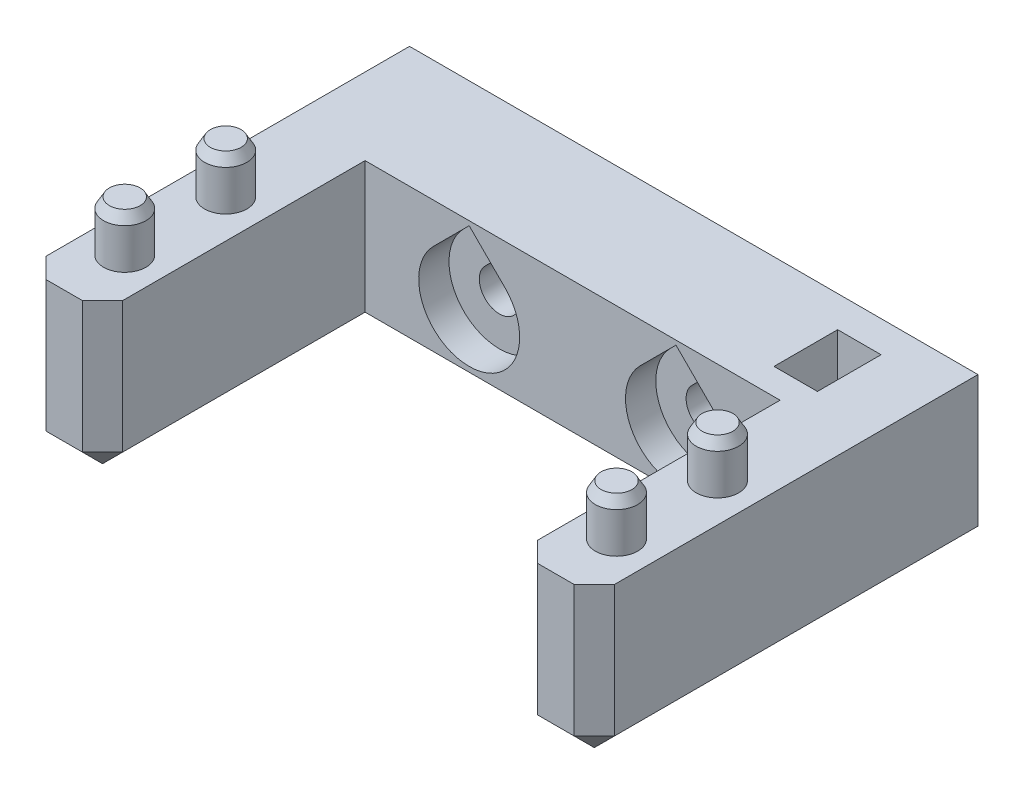
SolidWorks part; units mm, degrees
ref_plane "Front Plane" through (0, 0, 0) normal (0, 0, 1) x (1, 0, 0)
ref_plane "Top Plane" through (0, 0, 0) normal (0, 1, 0) x (1, 0, 0)
ref_plane "Right Plane" through (0, 0, 0) normal (1, 0, 0) x (0, 0, -1)
sketch "Sketch2" plane through (0, 0, 0) normal (0, 1, 0) x (1, 0, 0)
  line L0 (-22.25, 13.4082) -> (-22.25, -6080.7708) construction
  line L1 (-20.25, -10) -> (20.25, -10) construction
  line L2 (-20.25, -10) -> (-20.25, 10) construction
  line L3 (-20.25, 10) -> (20.25, 10) construction
  line L4 (20.25, -10) -> (20.25, 10) construction
  line L5 (-20.25, -10) -> (20.25, 10) construction
  line L6 (-20.25, 10) -> (20.25, -10) construction
  line L7 (0, 0) -> (-50000, 0) construction
  line L8 (-24.35, 2.9) -> (-24.35, -2.9) construction
  line L9 (0, 0) -> (0, 50000) construction
  circle A0 centre (-24.35, 5) radius 2.1
  circle A1 centre (-24.35, -5) radius 2.1
  circle A2 centre (24.35, -5) radius 2.1
  circle A3 centre (24.35, 5) radius 2.1
  point P0 (0, 0)
  point P12 (-24.35, 2.9)
  point P13 (-24.35, -2.9)
  point P18 (-24.35, 0)
  dimension "D2" = 4.2
  dimension "D1" = 2
  dimension "D3" = 40.5
  dimension "D4" = 20
  dimension "D5" = 5.8
extrude "Boss-Extrude1" add sketch "Sketch2" along normal blind 5
sketch "Sketch3" plane through (0, 0, 0) normal (0, 1, 0) x (1, 0, 0)
  line L0 (-20.25, -10) -> (-20.25, 10) construction
  line L1 (-28.15, -11) -> (-20.55, -11)
  line L2 (-28.15, -11) -> (-28.15, 15)
  line L3 (-28.15, 15) -> (-20.55, 15)
  line L4 (-20.55, -11) -> (-20.55, 15)
  line L5 (-28.15, -11) -> (-20.55, 15) construction
  line L6 (-28.15, 15) -> (-20.55, -11) construction
  line L7 (0, 0) -> (0, 50000) construction
  line L8 (28.15, -11) -> (28.15, 15)
  line L9 (28.15, -11) -> (20.55, -11)
  line L10 (20.55, -11) -> (20.55, 15)
  line L11 (28.15, 15) -> (20.55, 15)
  line L13 (200000, 0) -> (-250000, 0) construction
  point P0 (-24.35, 2)
  point P15 (0, 0)
  point P16 (-24.2905, 1.4461)
  point P17 (0, 0)
  point P18 (0, 0)
  point P22 (0, 0)
  dimension "D1" = 0.3
  dimension "D2" = 26
  dimension "D3" = 11
extrude "Boss-Extrude2" add sketch "Sketch3" against normal blind 15
chamfer "Chamfer1" distance 1 angle 30 2 edges at (-24.35, 5, -2.9) (-24.35, 5, 7.1)
chamfer "Chamfer2" distance 1 angle 30 2 edges at (24.35, 5, 2.9) (24.35, 5, -7.1)
sketch "Sketch4" plane through (0, 0, 0) normal (0, 1, 0) x (1, 0, 0)
  line L0 (-28.15, 15) -> (28.15, 15)
  line L1 (-28.15, 15) -> (-28.15, 27)
  line L2 (28.15, 15) -> (28.15, 27)
  line L3 (-28.15, 27) -> (28.15, 27)
  line L4 (28.15, 15) -> (20.55, 15) construction
  dimension "D1" = 12
extrude "Boss-Extrude3" add sketch "Sketch4" against normal up to surface (15 mm away) up to face at (-24.35, -15, -2)
sketch "Sketch5" plane through (0, 0, -15) normal (0, 0, 1) x (1, 0, 0)
  line L0 (0, 0) -> (0, -15) construction
  line L1 (-20.55, -15) -> (20.55, -15) construction
  line L2 (-10.2402, -7.5) -> (0, -7.5) construction
  line L3 (0, 0) -> (0, -50000) construction
  line L4 (-10.2402, -7.5) -> (-11.6544, -6.0858) construction
  line L5 (-10.2402, -7.5) -> (-8.8259, -6.0858) construction
  line L6 (-10.2402, -7.5) -> (-10.2402, 0) construction
  line L7 (-20.55, 0) -> (20.55, 0) construction
  line L8 (-11.6544, -6.0858) -> (-10.2402, -4.6716)
  line L9 (-10.2402, -4.6716) -> (-8.8259, -6.0858)
  line L10 (11.6544, -6.0858) -> (10.2402, -4.6716)
  line L11 (10.2402, -4.6716) -> (8.8259, -6.0858)
  line L12 (0, -7.5) -> (10.2402, -7.5) construction
  circle A0 centre (-10.2402, -7.5) radius 2 construction
  arc A1 (-11.6544, -6.0858) -> (-8.8259, -6.0858) centre (-10.2402, -7.5) ccw
  arc A2 (11.6544, -6.0858) -> (8.8259, -6.0858) centre (10.2402, -7.5) cw
  dimension "D1" = 4
extrude "Cut-Extrude1" cut sketch "Sketch5" against normal through all contours L8 A1 L9 | A2 L10 L11
sketch "Sketch6" plane through (0, 0, -15) normal (0, 0, 1) x (1, 0, 0)
  line L29 (-6.7046, -3.9645) -> (-10.2402, -0.4289)
  line L30 (-10.2402, -0.4289) -> (-13.7757, -3.9645)
  line L31 (-6.7046, -3.9645) -> (-10.2402, -0.4289)
  line L32 (-10.2402, -0.4289) -> (-13.7757, -3.9645)
  line L38 (13.7757, -3.9645) -> (10.2402, -0.4289)
  line L39 (10.2402, -0.4289) -> (6.7046, -3.9645)
  line L40 (13.7757, -3.9645) -> (10.2402, -0.4289)
  line L41 (10.2402, -0.4289) -> (6.7046, -3.9645)
  arc A13 (-13.7757, -3.9645) -> (-6.7046, -3.9645) centre (-10.2402, -7.5) ccw
  arc A14 (-13.7757, -3.9645) -> (-6.7046, -3.9645) centre (-10.2402, -7.5) ccw
  arc A16 (6.7046, -3.9645) -> (13.7757, -3.9645) centre (10.2402, -7.5) ccw
  arc A17 (6.7046, -3.9645) -> (13.7757, -3.9645) centre (10.2402, -7.5) ccw
  dimension "D1" = 3
  dimension "D2" = 3
extrude "Cut-Extrude2" cut sketch "Sketch6" against normal blind 3
chamfer "Chamfer7" distance 2 angle 45 12 edges at (0, -15, -15) (20.55, -15, -2) (20.55, -7.5, 11) (24.35, -15, 11) (28.15, -7.5, 11) (28.15, -15, -8) (0, -15, -27) (-28.15, -15, -8) (-28.15, -7.5, 11) (-24.35, -15, 11) (-20.55, -15, -2) (-20.55, -7.5, 11)
sketch "Sketch7" plane through (0, 0, 0) normal (0, 1, 0) x (1, 0, 0)
  line L0 (-20.55, 15) -> (20.55, 15) construction
  line L1 (21.65, 23.9) -> (17.35, 23.9)
  line L2 (21.65, 23.9) -> (21.65, 17.6)
  line L3 (21.65, 17.6) -> (17.35, 17.6)
  line L4 (17.35, 23.9) -> (17.35, 17.6)
  line L5 (21.65, 23.9) -> (17.35, 17.6) construction
  line L6 (21.65, 17.6) -> (17.35, 23.9) construction
  line L7 (28.15, -9) -> (28.15, 27) construction
  point P0 (19.5, 20.75)
  dimension "D1" = 6.3
  dimension "D2" = 4.3
  dimension "D3" = 2.6
  dimension "D4" = 6.5
extrude "Cut-Extrude3" cut sketch "Sketch7" against normal through all
